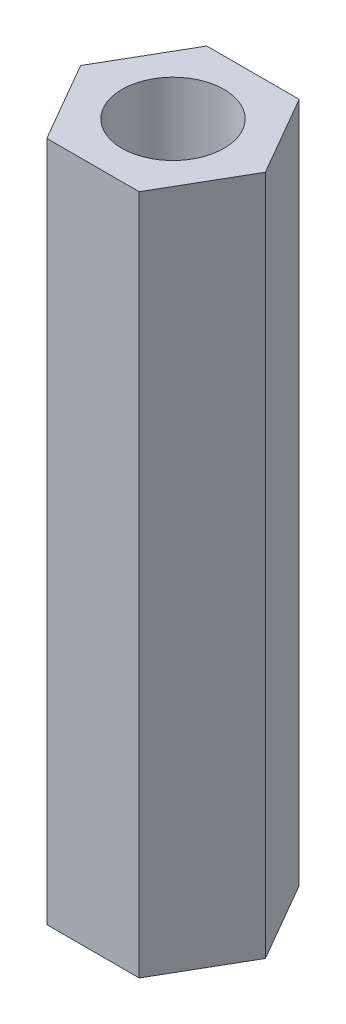
SolidWorks part; units mm, degrees
material "Brass"
ref_plane "Front Plane" through (0, 0, 0) normal (0, 0, 1) x (1, 0, 0)
ref_plane "Top Plane" through (0, 0, 0) normal (0, 1, 0) x (1, 0, 0)
ref_plane "Right Plane" through (0, 0, 0) normal (1, 0, 0) x (0, 0, -1)
sketch "Sketch1" plane through (0, 0, 0) normal (0, 1, 0) x (1, 0, 0)
  line L1 (2.7135, 0) -> (1.3568, 2.35)
  line L2 (1.3568, 2.35) -> (-1.3568, 2.35)
  line L3 (-1.3568, 2.35) -> (-2.7135, 0)
  line L4 (-2.7135, 0) -> (-1.3568, -2.35)
  line L5 (-1.3568, -2.35) -> (1.3568, -2.35)
  line L6 (1.3568, -2.35) -> (2.7135, 0)
  circle A0 centre (0, 0) radius 1.5
  circle A1 centre (0, 0) radius 2.35 construction
extrude "Boss-Extrude1" add sketch "Sketch1" along normal blind 20
